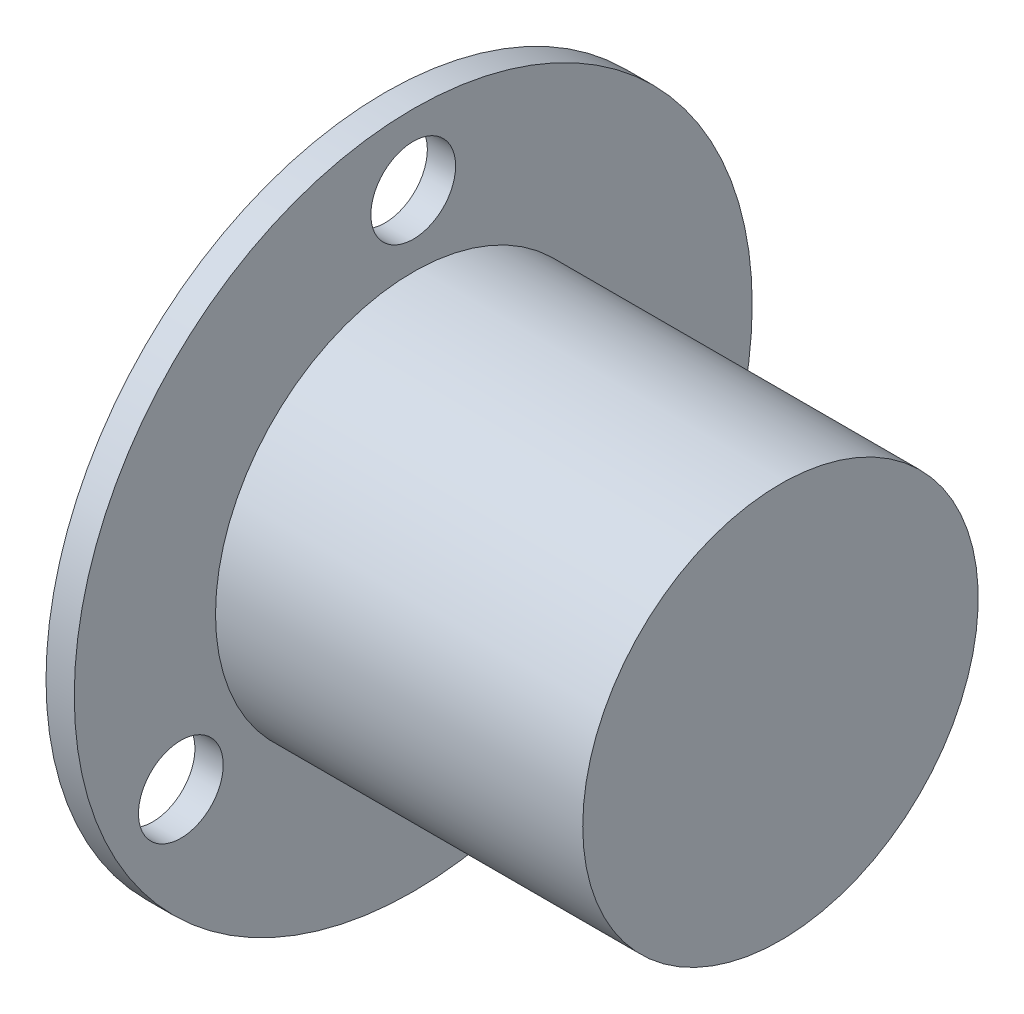
SolidWorks part; units mm, degrees
ref_plane "Front Plane" through (0, 0, 0) normal (0, 0, 1) x (1, 0, 0)
ref_plane "Top Plane" through (0, 0, 0) normal (0, 1, 0) x (1, 0, 0)
ref_plane "Right Plane" through (0, 0, 0) normal (1, 0, 0) x (0, 0, -1)
sketch "Sketch1" plane through (0, 0, 0) normal (1, 0, 0) x (0, 0, -1)
  circle A0 centre (0, 0) radius 12
  dimension "D1" = 24
extrude "Boss-Extrude1" add sketch "Sketch1" along normal blind 1
sketch "Sketch2" plane through (1, 0, 0) normal (1, 0, 0) x (0, 0, -1)
  circle A0 centre (0, 0) radius 7
  dimension "D1" = 14
extrude "Boss-Extrude2" add sketch "Sketch2" along normal blind 13
sketch "Sketch3" plane through (1, 0, 0) normal (1, 0, 0) x (0, 0, -1)
  line L0 (0, 12) -> (0, 7) construction
  circle A0 centre (0, 9.5) radius 1.5
  circle A1 centre (0, 0) radius 12 construction
  circle A2 centre (0, 0) radius 7 construction
  circle A4 centre (8.2272, -4.75) radius 1.5
  circle A5 centre (-8.2272, -4.75) radius 1.5
  point P16 (0, 0)
  dimension "D1" = 3
  dimension "D2" = 9.5
  dimension "D3" = 3
extrude "Cut-Extrude1" cut sketch "Sketch3" against normal blind 1
sketch "Sketch4" plane through (0, 0, 0) normal (-1, 0, 0) x (0, 0, 1)
  circle A0 centre (0, 0) radius 2.5
  dimension "D1" = 5
extrude "Boss-Extrude3" add sketch "Sketch4" along normal blind 5
